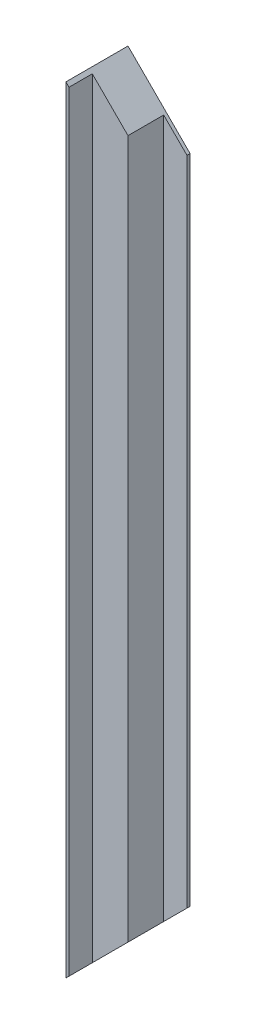
SolidWorks part; units mm, degrees
material "1060 Alloy"
ref_plane "Front Plane" through (0, 0, 0) normal (0, 0, 1) x (1, 0, 0)
ref_plane "Top Plane" through (0, 0, 0) normal (0, 1, 0) x (1, 0, 0)
ref_plane "Right Plane" through (0, 0, 0) normal (1, 0, 0) x (0, 0, -1)
sketch "Sketch2" plane through (0, 0, 0) normal (0, 0, 1) x (1, 0, 0)
  line L1 (-344.5977, 311.7816) -> (-304.5977, 311.7816)
  line L2 (-344.5977, 311.7816) -> (-344.5977, -188.2184)
  line L3 (-344.5977, -188.2184) -> (-304.5977, -188.2184)
  line L4 (-304.5977, 311.7816) -> (-304.5977, -188.2184)
  dimension "D1" = 500
  dimension "D2" = 40
extrude "Boss-Extrude1" add sketch "Sketch2" along normal blind 40
sketch "Sketch3" plane through (0, 311.7816, 0) normal (0, 1, 0) x (1, 0, 0)
  line L0 (-344.5977, -40) -> (-344.5977, 0) construction
  line L1 (-342.5977, -25) -> (-304.5977, -25)
  line L2 (-342.5977, -25) -> (-342.5977, -40)
  line L3 (-342.5977, -40) -> (-304.5977, -40)
  line L4 (-304.5977, -25) -> (-304.5977, -40)
  line L5 (-319.5977, -2) -> (-304.5977, -2)
  line L6 (-319.5977, -2) -> (-319.5977, -40)
  line L7 (-319.5977, -40) -> (-304.5977, -40)
  line L8 (-304.5977, -2) -> (-304.5977, -40)
  line L9 (-304.5977, 0) -> (-344.5977, 0) construction
  line L10 (-304.5977, -40) -> (-304.5977, 0) construction
  line L11 (-304.5977, -40) -> (-344.5977, -40) construction
  line M11 (-344.5977, -40) -> (-304.5977, -40)
  line M12 (-304.5977, -40) -> (-304.5977, 0)
  dimension "D1" = 2
  dimension "D2" = 2
  dimension "D3" = 0
  dimension "D4" = 0
  dimension "D5" = 25
  dimension "D6" = 25
  dimension "D7" = 0
  dimension "D8" = 0
extrude "Cut-Extrude1" cut sketch "Sketch3" against normal blind 1000 contours L5 L6 L1 M12 | L1 L6 L3 M12 | L6 L1 L2 M11
sketch "Sketch4" plane through (0, 0, 0) normal (0, 0, -1) x (-1, 0, 0)
  line L0 (304.5977, 311.7816) -> (344.5977, 311.7816)
  line L1 (344.5977, 311.7816) -> (304.5977, 271.7816)
  line L2 (304.5977, -188.2184) -> (304.5977, 311.7816) construction
  line L3 (304.5977, 271.7816) -> (304.5977, 311.7816)
  line L4 (344.5977, -188.2184) -> (304.5977, -188.2184)
  line L5 (304.5977, -188.2184) -> (304.5977, -148.2184)
  line L6 (304.5977, -148.2184) -> (344.5977, -188.2184)
  dimension "D1" = 40
  dimension "D2" = 40
extrude "Cut-Extrude2" cut sketch "Sketch4" against normal blind 1000
